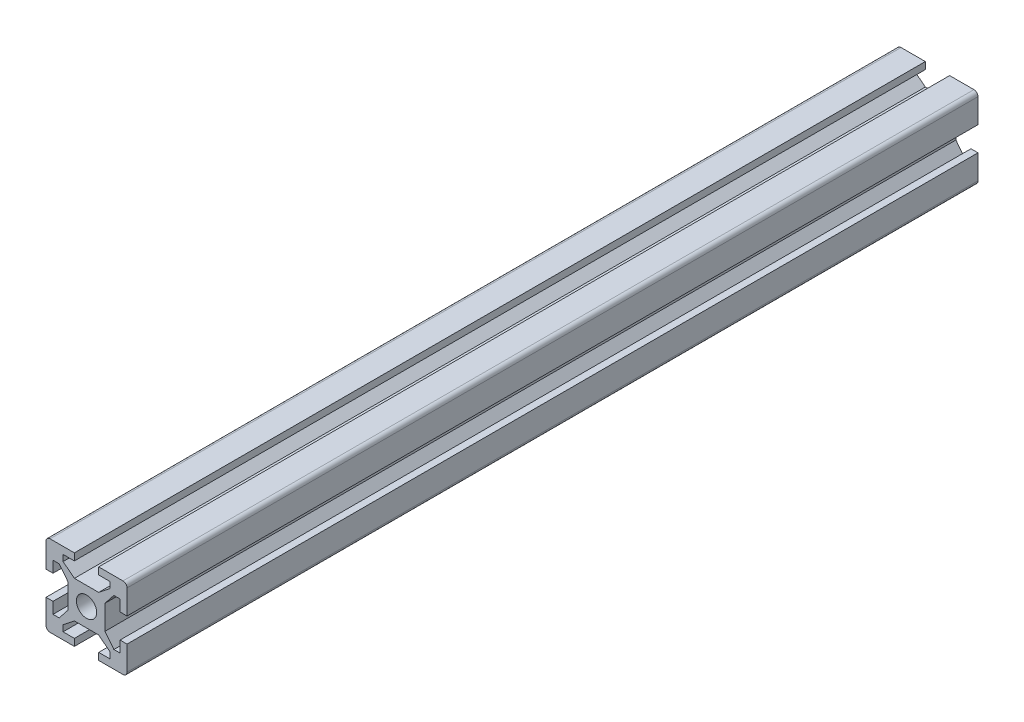
SolidWorks part; units mm, degrees
material "6063-T5"
ref_plane "Front Plane" through (0, 0, 0) normal (0, 0, 1) x (1, 0, 0)
ref_plane "Top Plane" through (0, 0, 0) normal (0, 1, 0) x (1, 0, 0)
ref_plane "Right Plane" through (0, 0, 0) normal (1, 0, 0) x (0, 0, -1)
sketch "Sketch1" plane through (0, 0, 0) normal (0, 0, 1) x (1, 0, 0)
  line L18 (0, 0) -> (0, 20.5117) construction
  line L39 (-10, 10) -> (-3, 10)
  line L41 (10, 10) -> (3, 10)
  line L43 (-10, 10) -> (-10, 3)
  line L45 (-10, -10) -> (-10, -3)
  line L47 (-10, -10) -> (-3, -10)
  line L49 (3, -10) -> (10, -10)
  line L51 (10, -10) -> (10, -3)
  line L53 (10, 3) -> (10, 10)
  line L55 (-3, 10) -> (-3, 8.2726)
  line L56 (-3, 8.2726) -> (-5.7838, 8.2726)
  line L57 (-5.7838, 8.2726) -> (-5.7838, 6.748)
  line L58 (-5.7838, 6.748) -> (-3, 4.5508)
  line L59 (-3, 4.5508) -> (3, 4.5508)
  line L60 (3, 10) -> (3, 8.2726)
  line L61 (3, 8.2726) -> (5.7838, 8.2726)
  line L62 (5.7838, 8.2726) -> (5.7838, 6.748)
  line L63 (5.7838, 6.748) -> (3, 4.5508)
  line L64 (10, 3) -> (8.2726, 3)
  line L65 (8.2726, 3) -> (8.2726, 5.7838)
  line L66 (8.2726, 5.7838) -> (6.748, 5.7838)
  line L67 (10, -3) -> (8.2726, -3)
  line L68 (8.2726, -3) -> (8.2726, -5.7838)
  line L69 (8.2726, -5.7838) -> (6.748, -5.7838)
  line L70 (4.55, -2.9994) -> (4.55, 3.0006)
  line L71 (4.55, -2.9994) -> (6.748, -5.7838)
  line L72 (4.55, 3.0006) -> (6.748, 5.7838)
  line L73 (3, -10) -> (3, -8.2726)
  line L74 (3, -8.2726) -> (5.7838, -8.2726)
  line L75 (5.7838, -8.2726) -> (5.7838, -6.748)
  line L76 (-3, -10) -> (-3, -8.2726)
  line L77 (-3, -8.2726) -> (-5.7838, -8.2726)
  line L78 (-5.7838, -8.2726) -> (-5.7838, -6.748)
  line L79 (2.9994, -4.55) -> (-3.0006, -4.55)
  line L80 (5.7838, -6.748) -> (2.9994, -4.55)
  line L81 (-5.7838, -6.748) -> (-3.0006, -4.55)
  line L82 (-10, -3) -> (-8.2726, -3)
  line L83 (-8.2726, -3) -> (-8.2726, -5.7838)
  line L84 (-8.2726, -5.7838) -> (-6.748, -5.7838)
  line L85 (-10, 3) -> (-8.2726, 3)
  line L86 (-8.2726, 3) -> (-8.2726, 5.7838)
  line L87 (-8.2726, 5.7838) -> (-6.748, 5.7838)
  line L88 (-4.55, -3.0006) -> (-4.55, 2.9994)
  line L89 (-6.748, -5.7838) -> (-4.55, -3.0006)
  line L90 (-4.55, 2.9994) -> (-6.748, 5.7838)
  dimension "D9" = 7
  dimension "D17" = 2.7838
  dimension "D1" = 20
  dimension "D2" = 20
  dimension "D3" = 10
  dimension "D4" = 10
  dimension "D5" = 7
  dimension "D6" = 7
  dimension "D7" = 7
  dimension "D8" = 7
  dimension "D10" = 7
  dimension "D11" = 7
  dimension "D12" = 7
  dimension "D13" = 6
  dimension "D14" = 3
  dimension "D15" = 3.5464
  dimension "D16" = 1.5246
  dimension "D18" = 1.7274
  dimension "D19" = 4.55
  dimension "D20" = 4.55
  dimension "D21" = 4.55
  dimension "D22" = 10
  dimension "D23" = 10
  dimension "D24" = 10
  dimension "D25" = 10
  dimension "D26" = 10
  dimension "D27" = 10
  dimension "D28" = 6
  dimension "D29" = 6
  dimension "D30" = 6
  dimension "D31" = 6
extrude "Boss-Extrude1" add sketch "Sketch1" along normal mid plane 210
sketch "Sketch2" plane through (0, 0, 105) normal (0, 0, 1) x (1, 0, 0)
  circle A0 centre (0, 0) radius 2.5
  dimension "D1" = 5
extrude "Cut-Extrude1" cut sketch "Sketch2" against normal through all both and the other way through all
fillet "Fillet1" radius 1 4 edges at (-10, -10, 0) (10, -10, 0) (10, 10, 0) (-10, 10, 0)
